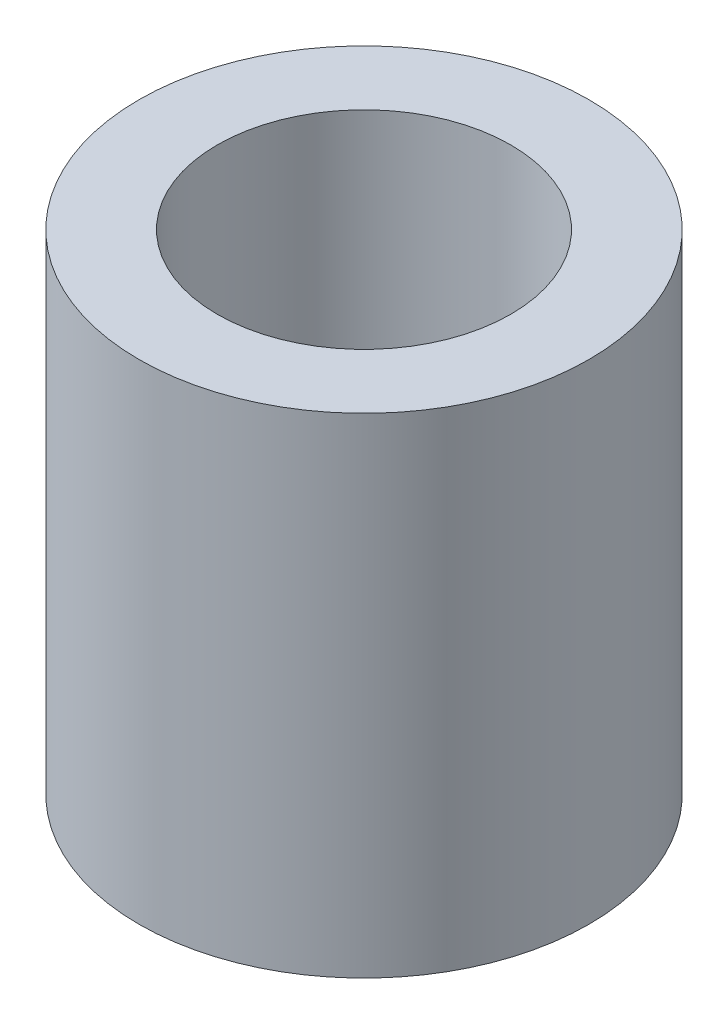
SolidWorks part; units mm, degrees
material "Custom Plastic"
ref_plane "Front Plane" through (0, 0, 0) normal (0, 0, 1) x (1, 0, 0)
ref_plane "Top Plane" through (0, 0, 0) normal (0, 1, 0) x (1, 0, 0)
ref_plane "Right Plane" through (0, 0, 0) normal (1, 0, 0) x (0, 0, -1)
sketch "Sketch1" plane through (0, 0, 0) normal (0, 0, 1) x (1, 0, 0)
  line L0 (0, 0) -> (0, 10.8941) construction
  line L2 (-1.5, 0) -> (-2.3, 0)
  line L3 (-1.5, 0) -> (-1.5, 5)
  line L4 (-1.5, 5) -> (-2.3, 5)
  line L5 (-2.3, 0) -> (-2.3, 5)
  dimension "D1" = 3
  dimension "D2" = 0.8
  dimension "D3" = 5
revolve "Revolve1" add sketch "Sketch1" angle 360 about L0
